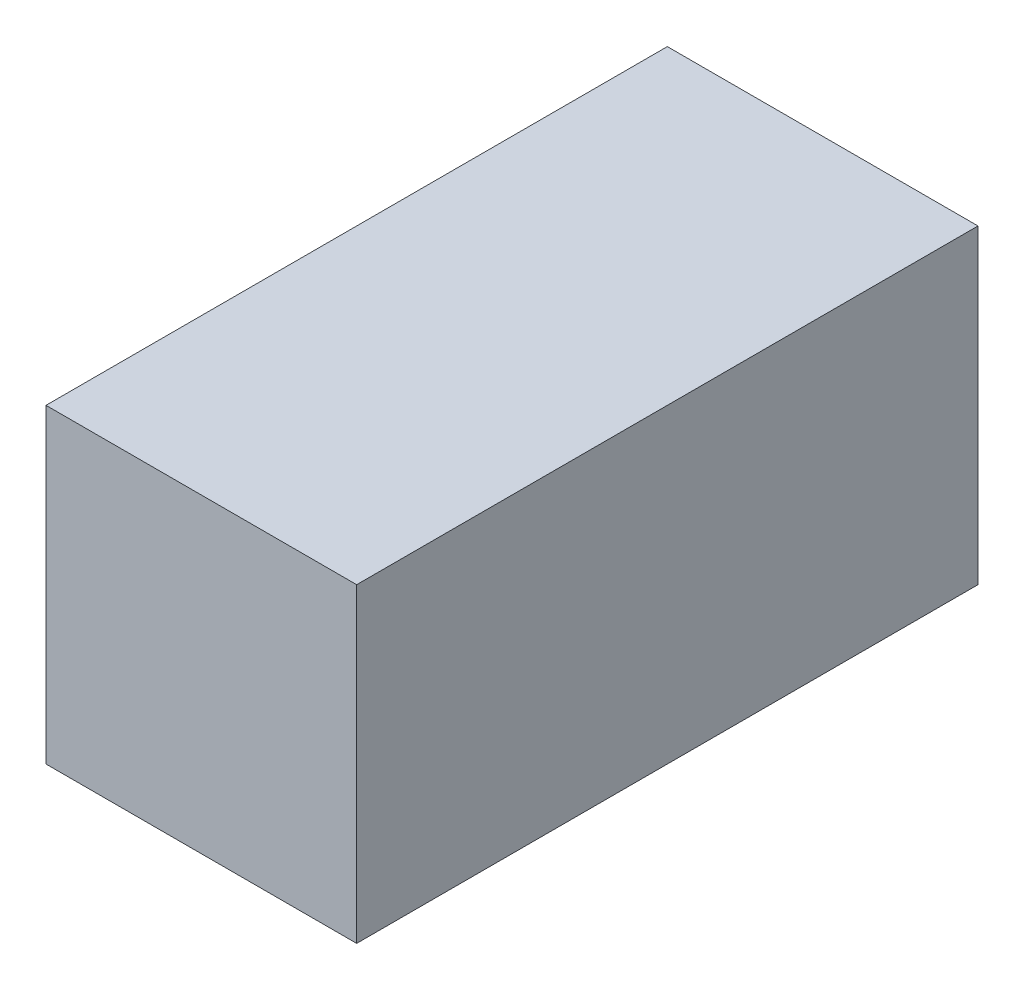
SolidWorks part; units mm, degrees
ref_plane "Front Plane" through (0, 0, 0) normal (0, 0, 1) x (1, 0, 0)
ref_plane "Top Plane" through (0, 0, 0) normal (0, 1, 0) x (1, 0, 0)
ref_plane "Right Plane" through (0, 0, 0) normal (1, 0, 0) x (0, 0, -1)
sketch "Sketch1" plane through (0, 0, 0) normal (0, 0, 1) x (1, 0, 0)
  line L1 (0, 0) -> (5.08, 0)
  line L2 (0, 0) -> (0, 5.08)
  line L3 (0, 5.08) -> (5.08, 5.08)
  line L4 (5.08, 0) -> (5.08, 5.08)
  dimension "D1" = 5.08
  dimension "D2" = 5.08
extrude "Boss-Extrude1" add sketch "Sketch1" along normal blind 10.16
